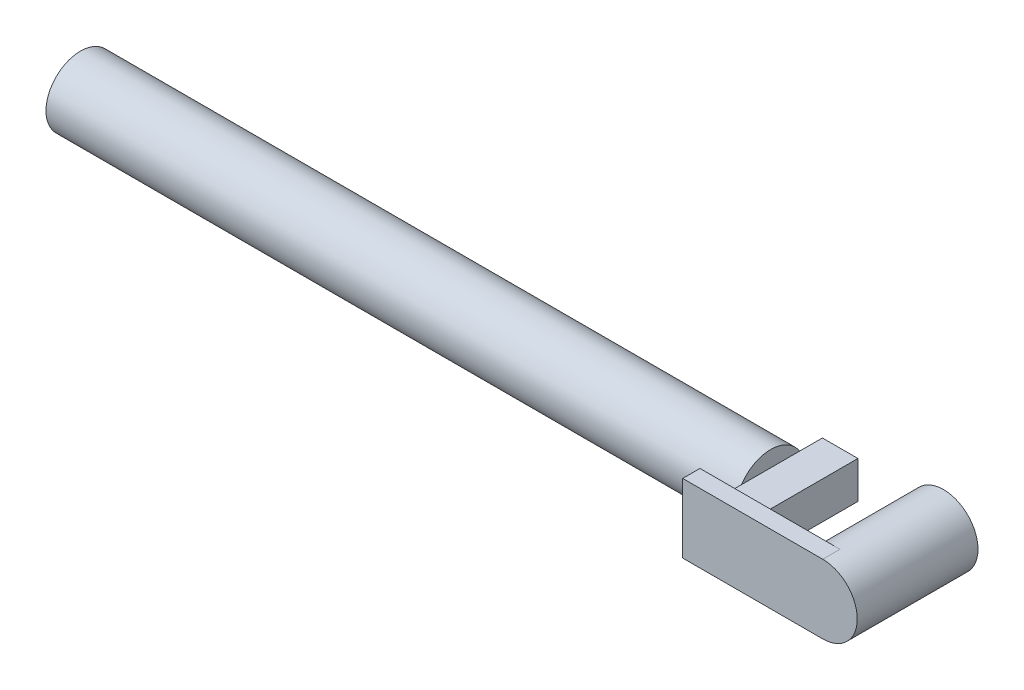
SolidWorks part; units mm, degrees
ref_plane "Płaszczyzna przednia" through (0, 0, 0) normal (0, 0, 1) x (1, 0, 0)
ref_plane "Płaszczyzna górna" through (0, 0, 0) normal (0, 1, 0) x (1, 0, 0)
ref_plane "Płaszczyzna prawa" through (0, 0, 0) normal (1, 0, 0) x (0, 0, -1)
sketch "Szkic1" plane through (0, 0, 0) normal (0, 0, 1) x (1, 0, 0)
  circle A0 centre (0, 0) radius 10
  dimension "D1" = 20
extrude "Dodanie-wyciągnięcie1" add sketch "Szkic1" along normal mid plane 30
sketch "Szkic2" plane through (0, 0, 15) normal (0, 0, 1) x (1, 0, 0)
  line L0 (0, 10) -> (-40.576, 10)
  line L1 (-40.576, 10) -> (-40.576, -10)
  line L2 (-40.576, -10) -> (0, -10)
  circle A0 centre (0, 0) radius 10 construction
  arc A1 (0, -10) -> (0, 10) centre (0, 0) ccw
extrude "Dodanie-wyciągnięcie2" add sketch "Szkic2" along normal blind 5
sketch "Szkic3" plane through (0, 0, 15) normal (0, 0, -1) x (-1, 0, 0)
  line L1 (24.798, -5.3917) -> (35.0937, -5.3917)
  line L2 (24.798, -5.3917) -> (24.798, 5.3917)
  line L3 (24.798, 5.3917) -> (35.0937, 5.3917)
  line L4 (35.0937, -5.3917) -> (35.0937, 5.3917)
  line L5 (24.798, -5.3917) -> (35.0937, 5.3917) construction
  line L6 (24.798, 5.3917) -> (35.0937, -5.3917) construction
  point P0 (29.9458, 0)
extrude "Dodanie-wyciągnięcie3" add sketch "Szkic3" along normal blind 30
sketch "Szkic4" plane through (-35.0937, 0, 0) normal (-1, 0, 0) x (0, 0, 1)
  circle A0 centre (0, 0) radius 10
  dimension "D1" = 20
extrude "Dodanie-wyciągnięcie4" add sketch "Szkic4" along normal blind 200
